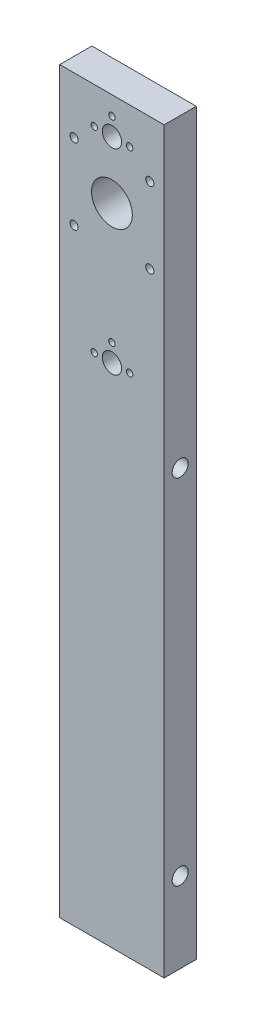
SolidWorks part; units mm, degrees
ref_plane "Front Plane" through (0, 0, 0) normal (0, 0, 1) x (1, 0, 0)
ref_plane "Top Plane" through (0, 0, 0) normal (0, 1, 0) x (1, 0, 0)
ref_plane "Right Plane" through (0, 0, 0) normal (1, 0, 0) x (0, 0, -1)
sketch "Sketch1" plane through (0, 0, 0) normal (0, 0, 1) x (1, 0, 0)
  line L0 (-18, -106) -> (18, -106) construction
  line L2 (-32.5, 38.575) -> (32.5, 38.575)
  line L3 (-42.5, 38.575) -> (42.5, 38.575) construction
  line L4 (-32.5, -371.425) -> (-32.5, 28.575) construction
  line L5 (32.5, -371.425) -> (32.5, 28.575) construction
  line L6 (-18, 16) -> (18, 16) construction
  line L8 (23.5712, -43.5712) -> (-23.5712, -43.5712) construction
  line L9 (23.5712, -43.5712) -> (23.5712, 3.5712) construction
  line L10 (23.5712, 3.5712) -> (-23.5712, 3.5712) construction
  line L11 (-23.5712, -43.5712) -> (-23.5712, 3.5712) construction
  line L12 (23.5712, -43.5712) -> (-23.5712, 3.5712) construction
  line L13 (23.5712, 3.5712) -> (-23.5712, -43.5712) construction
  line L14 (-32.5, -421.425) -> (32.5, -421.425)
  line L16 (-32.5, -421.425) -> (-32.5, 38.575)
  line L18 (32.5, -421.425) -> (32.5, 38.575)
  line L21 (-42.5, -381.425) -> (-42.5, 38.575) construction
  line L22 (42.5, -381.425) -> (42.5, 38.575) construction
  line L23 (-32.5, 28.575) -> (32.5, 28.575) construction
  line L24 (-42.5, -381.425) -> (42.5, -381.425) construction
  line L25 (-32.5, -371.425) -> (-32.5, 38.575) construction
  line L26 (-82.5, -421.425) -> (82.5, -421.425) construction
  line L27 (32.5, -371.425) -> (32.5, 38.575) construction
  line L28 (-32.5, -371.425) -> (32.5, -371.425) construction
  line L29 (82.5, -421.425) -> (82.5, 88.575) construction
  line L30 (-82.5, -421.425) -> (-82.5, 88.575) construction
  line L31 (-82.5, 88.575) -> (82.5, 88.575) construction
  circle A0 centre (-23.5712, 3.5712) radius 2.54
  circle A1 centre (23.5712, 3.5712) radius 2.54
  circle A2 centre (23.5712, -43.5712) radius 2.54
  circle A3 centre (-23.5712, -43.5712) radius 2.54
  circle A4 centre (0, -20) radius 28.575 construction
  circle A5 centre (0, -106) radius 6
  circle A6 centre (0, -106) radius 11 construction
  circle A7 centre (11, -106) radius 2
  circle A8 centre (0, -20) radius 12.7
  circle A10 centre (0, -95) radius 2
  circle A12 centre (0, 16) radius 6
  circle A13 centre (11, 16) radius 2
  circle A14 centre (-11, -106) radius 2
  circle A15 centre (0, 27) radius 2
  circle A16 centre (-11, 16) radius 2
  circle A17 centre (0, 16) radius 11 construction
  point P0 (0, -20)
  point P8 (0, -20)
  dimension "D5" = 5.08
  dimension "D7" = 460
  dimension "D8" = 36
  dimension "D9" = 2
  dimension "D2" = 25.4
  dimension "D6" = 57.15
  dimension "D1" = 65
  dimension "D3" = 47.1424
  dimension "D4" = 47.1424
  dimension "D10" = 122
  dimension "D11" = 315.425
extrude "Boss-Extrude1" add sketch "Sketch1" along normal blind 20
sketch "Sketch2" plane through (0, 0, 0) normal (1, 0, 0) x (0, 0, -1)
  line L0 (-20, -371.425) -> (0, -371.425) construction
  line L1 (0, -421.425) -> (0, 38.575) construction
  line L2 (-20, -151.425) -> (0, -151.425) construction
  circle A0 centre (-10, -151.425) radius 5
  circle A1 centre (-10, -371.425) radius 5
extrude "Cut-Extrude1" cut sketch "Sketch2" against normal mid plane 80
